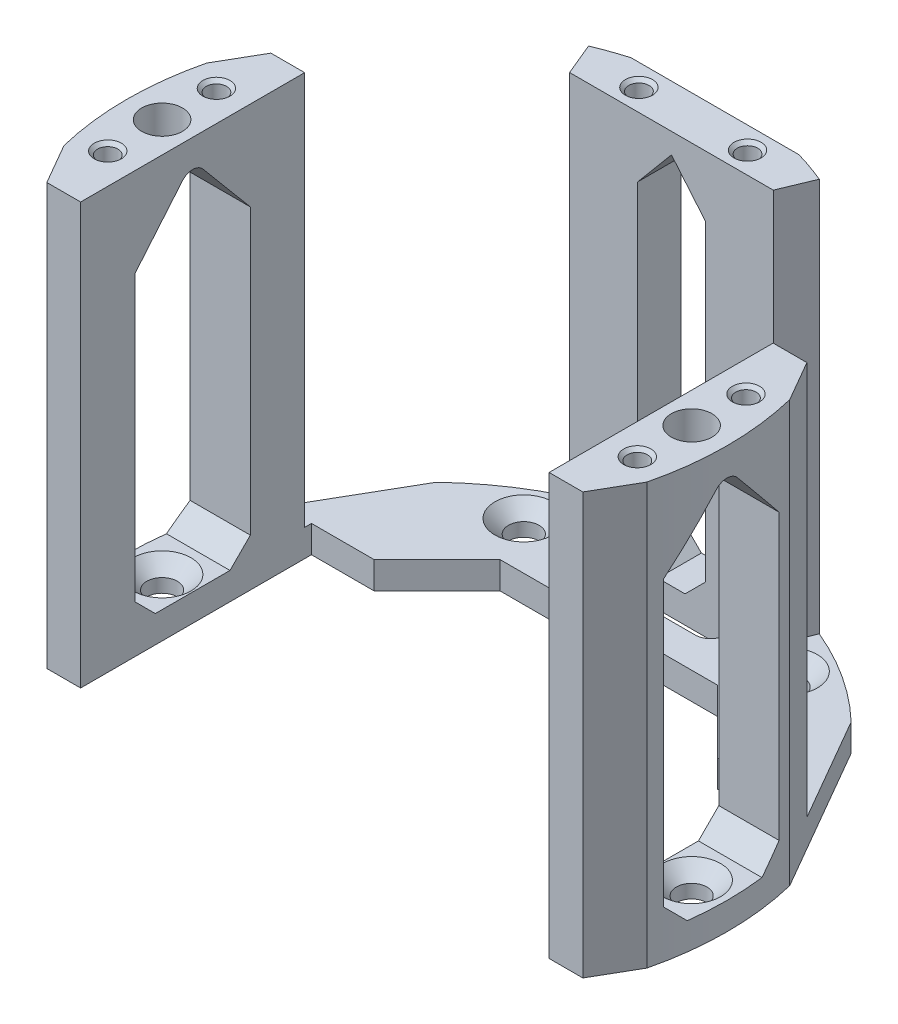
SolidWorks part; units mm, degrees
ref_plane "Спереди" through (0, 0, 0) normal (0, 0, 1) x (1, 0, 0)
ref_plane "Сверху" through (0, 0, 0) normal (0, 1, 0) x (1, 0, 0)
ref_plane "Справа" through (0, 0, 0) normal (1, 0, 0) x (0, 0, -1)
sketch "Эскиз1" plane through (0, 0, 0) normal (0, 1, 0) x (1, 0, 0)
  line L6 (0, -1000) -> (0, 49000) construction
  line L7 (19.5, 33.775) -> (0, 33.775) construction
  line L8 (33.5, 16.5) -> (16.5, 16.5) construction
  line L9 (8, 33.775) -> (8, 31.525) construction
  line L10 (8, 36.025) -> (-8, 36.025)
  line L11 (8, 36.025) -> (8, 33.775) construction
  line L12 (8, 31.525) -> (-8, 31.525)
  line L13 (-8, 36.025) -> (-8, 33.775) construction
  line L14 (8, 36.025) -> (-8, 31.525) construction
  line L15 (8, 31.525) -> (-8, 36.025) construction
  line L16 (-8, 33.775) -> (-8, 31.525) construction
  line L17 (0, 33.775) -> (-8, 33.775) construction
  line L18 (-8, 33.775) -> (-19.5, 33.775) construction
  line L19 (-16.5, 16.5) -> (-33.5, 16.5) construction
  line L28 (-30.5017, -32.0439) -> (-42.9308, -10.5161)
  line L29 (42.9308, -10.5161) -> (30.5017, -32.0439)
  line L30 (30.5726, 31.9211) -> (42.9308, 10.5161)
  line L31 (-12.3582, 42.4372) -> (12.3582, 42.4372)
  line L32 (-42.9308, 10.5161) -> (-30.5726, 31.9211)
  line L33 (-39.476, -16.5) -> (-42.9308, -10.5161)
  line L34 (42.9308, -10.5161) -> (30.5017, -32.0439)
  line L35 (30.5726, 31.9211) -> (42.9308, 10.5161)
  line L36 (-12.3582, 42.4372) -> (12.3582, 42.4372)
  line L37 (-42.9308, 10.5161) -> (-30.5726, 31.9211)
  line L40 (33.5, 16.5) -> (16.5, 16.5) construction
  line L41 (-16.5, 16.5) -> (-33.5, 16.5) construction
  line L42 (33.5, -16.5) -> (33.5, -3.5) construction
  line L43 (33.5, 3.5) -> (33.5, 16.5) construction
  line L44 (-33.5, -3.5) -> (-33.5, -16.5) construction
  line L45 (-33.5, 16.5) -> (-33.5, 3.5) construction
  line L46 (33.5, -16.5) -> (33.5, -3.5) construction
  line L47 (33.5, 3.5) -> (33.5, 16.5) construction
  line L48 (-33.5, -3.5) -> (-33.5, -16.5) construction
  line L49 (-33.5, 16.5) -> (-33.5, 3.5) construction
  line L50 (-34.5, -3.5) -> (-34.5, -16.5)
  line L51 (-25.275, 17.5) -> (-34.5, 17.5)
  line L52 (-34.5, 17.5) -> (-34.5, 3.5)
  line L53 (34.5, 3.5) -> (34.5, 17.5)
  line L54 (34.5, 17.5) -> (25.275, 17.5)
  line L55 (34.5, -16.5) -> (34.5, -3.5)
  line L56 (-34.5, 3.5) -> (-34.5, -3.5)
  line L57 (-34.5, -16.5) -> (-39.476, -16.5)
  line L58 (-30.5017, -32.0439) -> (-39.476, -16.5) construction
  line L59 (34.5, -16.5) -> (39.476, -16.5)
  line L60 (34.5, 3.5) -> (34.5, -3.5)
  line L61 (-16, 26.775) -> (16, 26.775)
  line L62 (-16, 26.775) -> (-25.275, 17.5)
  line L63 (25.275, 17.5) -> (16, 26.775)
  line L64 (-16.5, 17.5) -> (-25.275, 17.5) construction
  line L65 (-16.5, 17.5) -> (-34.5, 17.5) construction
  line L66 (25.275, 17.5) -> (16.5, 17.5) construction
  line L67 (34.5, 17.5) -> (16.5, 17.5) construction
  circle A0 centre (-19.5, 33.775) radius 2.25 construction
  circle A1 centre (19.5, 33.775) radius 2.25 construction
  circle A2 centre (-19.5, 33.775) radius 2.25
  circle A3 centre (19.5, 33.775) radius 2.25
  arc A4 (-12.5, 43.4372) -> (-31.3677, 32.5439) centre (0, 0) ccw construction
  arc A10 (-8, 31.525) -> (-8, 36.025) centre (-8, 33.775) cw
  arc A11 (8, 31.525) -> (8, 36.025) centre (8, 33.775) ccw
  circle A12 centre (39, 0) radius 2.25 construction
  circle A13 centre (-39, 0) radius 2.25 construction
  circle A14 centre (39, 0) radius 2.25
  circle A15 centre (-39, 0) radius 2.25
  arc A22 (-42.9308, 10.5161) -> (-42.9308, -10.5161) centre (0, 0) ccw
  arc A23 (42.9308, -10.5161) -> (42.9308, 10.5161) centre (0, 0) ccw
  arc A24 (30.5726, 31.9211) -> (12.3582, 42.4372) centre (0, 0) ccw
  arc A25 (-12.3582, 42.4372) -> (-30.5726, 31.9211) centre (0, 0) ccw
  arc A26 (-42.9308, 10.5161) -> (-42.9308, -10.5161) centre (0, 0) ccw
  arc A27 (42.9308, -10.5161) -> (42.9308, 10.5161) centre (0, 0) ccw
  arc A28 (30.5726, 31.9211) -> (12.3582, 42.4372) centre (0, 0) ccw
  arc A29 (-12.3582, 42.4372) -> (-30.5726, 31.9211) centre (0, 0) ccw
  point P25 (0, 33.775)
  dimension "D2" = 1
  dimension "D3" = 16
  dimension "D4" = 45
  dimension "D5" = 7
  dimension "D6" = 32
  dimension "D1" = 1
extrude "Бобышка-Вытянуть1" add sketch "Эскиз1" along normal blind 4 contours L36 A29 L37 A26 L33 L57 L50 L56 L52 L51 L62 L61 L63 L54 L53 L60 L55 L59 L34 A27 L35 A28 A2 A3 A11 L12 A10 L10 A14 A15
sketch "Эскиз2" plane through (0, 4, 0) normal (0, 1, 0) x (1, 0, 0)
  line L0 (-1000, 0) -> (49000, 0) construction
  line L1 (0, -1000) -> (0, 49000) construction
  line L2 (-43.375, -8.5) -> (-34.5, -8.5)
  line L3 (43.375, -8.5) -> (34.5, -8.5)
  line L4 (34.5, -16.5) -> (34.5, 17.5) construction
  line L5 (34.5, -16.5) -> (39.476, -16.5) construction
  line L6 (42.9308, -10.5161) -> (39.476, -16.5) construction
  line L7 (34.5, -16.5) -> (34.5, -8.5)
  line L8 (34.5, -16.5) -> (39.476, -16.5)
  line L9 (42.9308, -10.5161) -> (39.476, -16.5)
  line L10 (-34.5, 17.5) -> (-34.5, -16.5) construction
  line L11 (-34.5, -16.5) -> (-39.476, -16.5) construction
  line L12 (-39.476, -16.5) -> (-42.9308, -10.5161) construction
  line L13 (-34.5, -8.5) -> (-34.5, -16.5)
  line L14 (-34.5, -16.5) -> (-39.476, -16.5)
  line L15 (-39.476, -16.5) -> (-42.9308, -10.5161)
  line L16 (42.9308, 10.5161) -> (39.476, 16.5)
  line L17 (34.5, 16.5) -> (39.476, 16.5)
  line L18 (34.5, 16.5) -> (34.5, 8.5)
  line L19 (43.375, 8.5) -> (34.5, 8.5)
  line L20 (-34.5, 16.5) -> (-39.476, 16.5)
  line L21 (-34.5, 8.5) -> (-34.5, 16.5)
  line L22 (-43.375, 8.5) -> (-34.5, 8.5)
  line L23 (-39.476, 16.5) -> (-42.9308, 10.5161)
  arc A0 (42.9308, -10.5161) -> (42.9308, 10.5161) centre (0, 0) ccw construction
  arc A1 (42.9308, -10.5161) -> (43.375, -8.5) centre (0, 0) ccw
  arc A3 (42.9308, 10.5161) -> (43.375, 8.5) centre (0, 0) cw
  arc A4 (-43.375, -8.5) -> (-42.9308, -10.5161) centre (0, 0) ccw
  arc A5 (-43.375, 8.5) -> (-42.9308, 10.5161) centre (0, 0) cw
  line M21 (-30.5726, 31.9211) -> (-42.9308, 10.5161)
  arc M22 (-42.9308, 10.5161) -> (-42.9308, -10.5161) centre (0, 0) ccw
  line M23 (-42.9308, -10.5161) -> (-39.476, -16.5)
  line M24 (-39.476, -16.5) -> (-34.5, -16.5)
  line M25 (-34.5, -16.5) -> (-34.5, 17.5)
  line M31 (34.5, 17.5) -> (34.5, -16.5)
  line M32 (34.5, -16.5) -> (39.476, -16.5)
  line M33 (39.476, -16.5) -> (42.9308, -10.5161)
  arc M34 (42.9308, -10.5161) -> (42.9308, 10.5161) centre (0, 0) ccw
  line M35 (42.9308, 10.5161) -> (30.5726, 31.9211)
  dimension "D1" = 8
extrude "Бобышка-Вытянуть2" add sketch "Эскиз2" along normal blind 58 contours L22 L20 M22 M25 M21 | L2 M22 M23 M24 M25 | L19 L17 M34 M35 M31 | L3 M34 M31 M32 M33
sketch "Эскиз3" plane through (-34.5, 0, 0) normal (1, 0, 0) x (0, 0, -1)
  line L4 (-8.5, 62) -> (8.5, 62)
  line L5 (-8.5, 48.8701) -> (0, 59)
  line L8 (8.5, 62) -> (8.5, 4) construction
  line L9 (-8.5, 62) -> (-8.5, 4) construction
  line L10 (8.5, 62) -> (8.5, 48.8701)
  line L11 (-8.5, 62) -> (-8.5, 48.8701)
  line L12 (0, 59) -> (8.5, 48.8701)
  line L13 (0, -1000) -> (0, 49000) construction
  dimension "D1" = 40
  dimension "D2" = 3
extrude "Бобышка-Вытянуть3" add sketch "Эскиз3" against normal up to surface (8.875 mm away)
mirror "Зеркальное отражение1" about plane through (0, 0, 0) normal (1, 0, 0) of "Бобышка-Вытянуть3"
sketch "Эскиз4" plane through (0, 62, 0) normal (0, 1, 0) x (1, 0, 0)
  circle A0 centre (39, 0) radius 2.25 construction
  circle A1 centre (-39, 0) radius 2.25 construction
  circle A2 centre (39, 0) radius 2.25 construction
  circle A3 centre (-39, 0) radius 2.25 construction
  circle A4 centre (-39, 0) radius 3
  circle A5 centre (39, 0) radius 3
  dimension "D1" = 6
extrude "Вырез-Вытянуть1" cut sketch "Эскиз4" against normal up to surface (58 mm away) up to face at (39, 4, 2.25)
fillet "Скругление1" radius 2 4 edges at (35.25, 59, 0) (43.1, 59, 0) (-43.1, 59, 0) (-35.25, 59, 0)
chamfer "Фаска1" distance 2 angle 45 4 edges at (39, 4, 2.25) (19.5, 4, -31.525) (-19.5, 4, -31.525) (-39, 4, 2.25)
sketch "Эскиз6" plane through (0, 4, 0) normal (0, 1, 0) x (1, 0, 0)
  line L0 (8, 36.025) -> (-8, 36.025) construction
  line L1 (8, 36.025) -> (5, 36.025)
  line L2 (-12.3582, 42.4372) -> (12.3582, 42.4372) construction
  line L3 (-12.3582, 42.4372) -> (-5, 42.4372)
  line L5 (-15, 36.025) -> (-8, 36.025)
  line L7 (15, 36.025) -> (8, 36.025)
  line L8 (-15, 36.025) -> (-16.9899, 40.8042)
  line L9 (15, 36.025) -> (16.9899, 40.8042)
  line L10 (0, -1000) -> (0, 49000) construction
  line L11 (-5, 42.4372) -> (-5, 36.025)
  line L12 (5, 42.4372) -> (5, 36.025)
  line L13 (5, 36.025) -> (0, 36.025) construction
  line L14 (-5, 36.025) -> (-8, 36.025)
  line L15 (0, 42.4372) -> (5, 42.4372) construction
  line L16 (5, 42.4372) -> (12.3582, 42.4372)
  line L17 (-5, 42.4372) -> (0, 42.4372) construction
  line L18 (0, 36.025) -> (-5, 36.025) construction
  arc A2 (-12.3582, 42.4372) -> (-30.5726, 31.9211) centre (0, 0) ccw construction
  arc A3 (30.5726, 31.9211) -> (12.3582, 42.4372) centre (0, 0) ccw construction
  arc A4 (-12.3582, 42.4372) -> (-16.9899, 40.8042) centre (0, 0) ccw
  arc A5 (16.9899, 40.8042) -> (12.3582, 42.4372) centre (0, 0) ccw
  dimension "D1" = 30
  dimension "D2" = 10
extrude "Бобышка-Вытянуть4" add sketch "Эскиз6" along normal up to surface (58 mm away) up to face at (39, 62, 3)
sketch "Эскиз7" plane through (0, 0, -36.025) normal (0, 0, 1) x (1, 0, 0)
  line L0 (-5, 62) -> (-5, 4) construction
  line L1 (-5, 62) -> (-5, 53.0412)
  line L2 (5, 62) -> (5, 4) construction
  line L3 (5, 62) -> (5, 53.0412)
  line L4 (0, -1000) -> (0, 49000) construction
  line L5 (-5, 53.0412) -> (0, 59)
  line L6 (0, 59) -> (5, 53.0412)
  line L7 (-5, 62) -> (5, 62)
  line L8 (-5, 53.0412) -> (-5, 4) construction
  line L9 (5, 53.0412) -> (5, 4) construction
  dimension "D1" = 40
  dimension "D2" = 3
extrude "Бобышка-Вытянуть5" add sketch "Эскиз7" against normal up to surface (6.4122 mm away) up to face at (0, 32, -42.4372)
sketch "Эскиз8" plane through (0, 62, 0) normal (0, 1, 0) x (1, 0, 0)
  line L0 (0, -1000) -> (0, 49000) construction
  line L1 (-1000, 0) -> (49000, 0) construction
  line L2 (39, -1000) -> (39, 49000) construction
  line L3 (-1000, 39.2311) -> (49000, 39.2311) construction
  line L4 (12.3582, 42.4372) -> (-12.3582, 42.4372) construction
  line L5 (-15, 36.025) -> (15, 36.025) construction
  circle A0 centre (39, 0) radius 3 construction
  circle A1 centre (39, 0) radius 3 construction
  circle A2 centre (39, 8) radius 1.5
  circle A3 centre (8, 39.2311) radius 1.5
  circle A4 centre (39, -8) radius 1.5
  circle A5 centre (-8, 39.2311) radius 1.5
  circle A6 centre (-39, -8) radius 1.5
  circle A7 centre (-39, 8) radius 1.5
  dimension "D1" = 3
  dimension "D2" = 16
  dimension "D3" = 16
extrude "Вырез-Вытянуть2" cut sketch "Эскиз8" against normal blind 5
chamfer "Фаска2" distance 0.5 angle 45 6 edges at (-39, 62, 9.5) (-39, 62, -9.5) (-8, 62, -40.7311) (8, 62, -37.7311) (39, 62, -6.5) (39, 62, 6.5)
chamfer "Фаска3" distance 3 angle 45 6 edges at (38.9375, 4, -8.5) (38.9375, 4, 8.5) (-38.9375, 4, 8.5) (-38.9375, 4, -8.5) (-5, 4, -39.2311) (5, 4, -39.2311)
